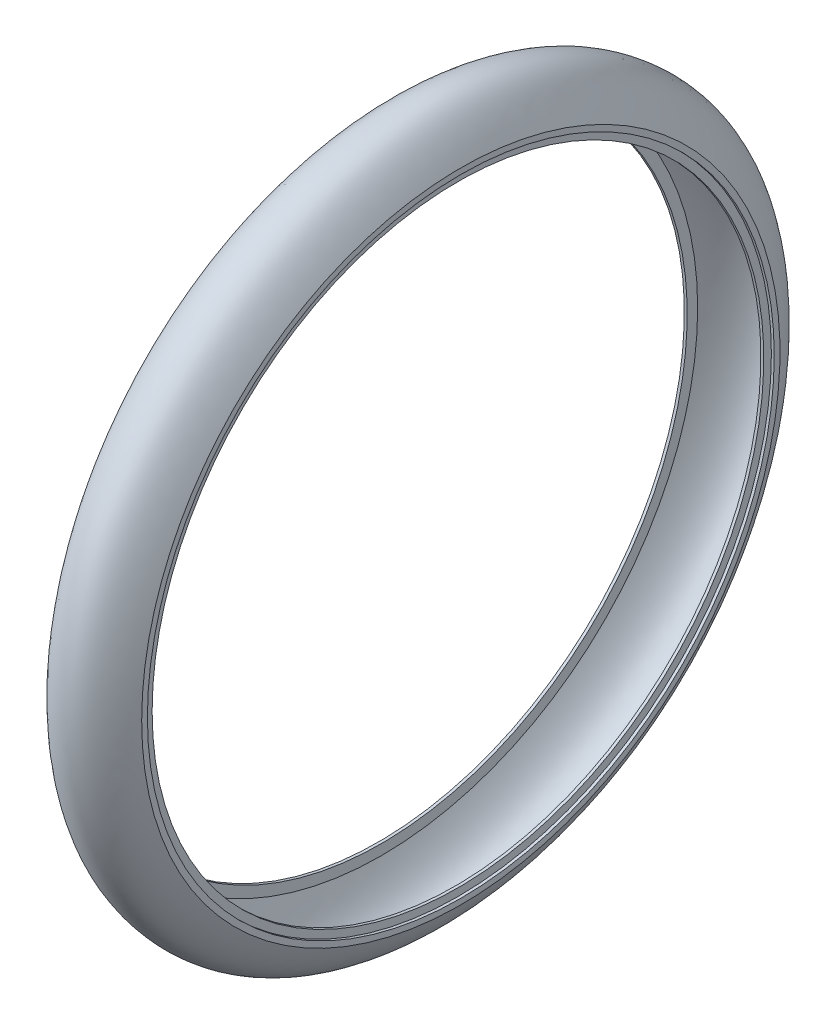
SolidWorks part; units mm, degrees
ref_plane "Front Plane" through (0, 0, 0) normal (0, 0, 1) x (1, 0, 0)
ref_plane "Top Plane" through (0, 0, 0) normal (0, 1, 0) x (1, 0, 0)
ref_plane "Right Plane" through (0, 0, 0) normal (1, 0, 0) x (0, 0, -1)
sketch "Sketch2" plane through (0, 0, 0) normal (0, 0, 1) x (1, 0, 0)
  line L0 (-88.5205, 0) -> (106.5575, 0) construction
  line L1 (0, 0) -> (0, 252.3558) construction
  line L2 (-27.7558, 213.69) -> (-27.7558, 219)
  line L3 (-27.7558, 219) -> (-29.7558, 219)
  line L4 (-29.7558, 219) -> (-29.7558, 223)
  line L5 (29.7558, 219) -> (29.7558, 223)
  line L6 (27.7558, 219) -> (29.7558, 219)
  line L7 (27.7558, 213.69) -> (27.7558, 219)
  line L8 (-25.7558, 213.69) -> (-25.7558, 221)
  line L9 (-25.7558, 221) -> (-27.7558, 221)
  line L10 (-27.7558, 221) -> (-27.7558, 221)
  line L11 (27.7558, 221) -> (27.7558, 221)
  line L12 (25.7558, 221) -> (27.7558, 221)
  line L13 (25.7558, 213.69) -> (25.7558, 221)
  line L14 (-27.7558, 213.69) -> (-25.7558, 213.69)
  line L15 (25.7558, 213.69) -> (27.7558, 213.69)
  line L16 (-29.7558, 223) -> (29.7558, 223) construction
  line L17 (-27.7558, 221) -> (27.7558, 221) construction
  spline S0 degree 3 poles (-29.7558, 223) (-20.3764, 241.4634) (-12.301, 249.2166) (9.1557, 250.7085) (18.6551, 243.6938) (29.7558, 223) knots 0 0 0 0 0.504858 0.604858 1 1 1 1
  spline S1 degree 2 poles (-27.7558, 221) (0, 275) (27.7558, 221) knots 0 0 0 1 1 1
  point P5 (0, 210)
  point P6 (-27.7558, 213.69)
  point P7 (-27.7558, 219)
  point P8 (-29.7558, 219)
  point P17 (0, 250)
  point P27 (29.7558, 223)
  point P28 (0, 248)
  dimension "D10" = 2
  dimension "D1" = 210
  dimension "D2" = 28
  dimension "D3" = 5.31
  dimension "D4" = 2
  dimension "D5" = 4
  dimension "D7" = 250
  dimension "D8" = 223
  dimension "D9" = 5.31
  dimension "D6" = 2
revolve "Revolve2" add sketch "Sketch2" angle 360 about L0
